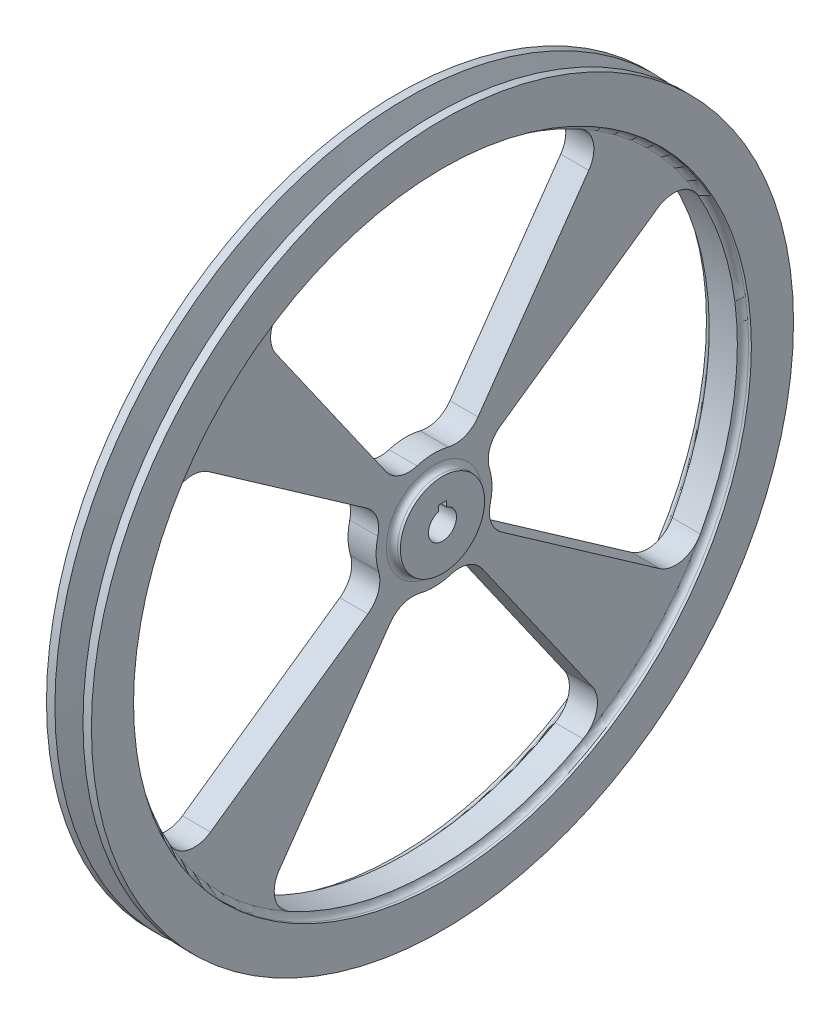
SolidWorks part; units mm, degrees
material "Alloy Steel (SS)"
ref_plane "Front Plane" through (0, 0, 0) normal (0, 0, 1) x (1, 0, 0)
ref_plane "Top Plane" through (0, 0, 0) normal (0, 1, 0) x (1, 0, 0)
ref_plane "Right Plane" through (0, 0, 0) normal (1, 0, 0) x (0, 0, -1)
sketch "Sketch1" plane through (0, 0, 0) normal (0, 1, 0) x (1, 0, 0)
  line L0 (-5, 15) -> (-5, 110)
  line L1 (-5, 110) -> (-8, 110)
  line L2 (-8, 110) -> (-8, 125)
  line L12 (8, 125) -> (8, 110)
  line L13 (8, 110) -> (5, 110)
  line L14 (5, 110) -> (5, 15)
  line L15 (5, 15) -> (8, 15)
  line L16 (8, 15) -> (8, 5)
  line L17 (8, 5) -> (-8, 5)
  line L18 (-8, 5) -> (-8, 15)
  line L19 (-8, 15) -> (-5, 15)
  line L20 (0, 0) -> (0, 100) construction
  line L21 (0, 0) -> (-66.9649, 0) construction
  line L22 (-5, 125) -> (-1.9427, 115)
  line L23 (-5, 125) -> (-8, 125)
  line L24 (5, 125) -> (8, 125)
  line L25 (-1.9427, 115) -> (1.9427, 115)
  line L26 (1.9427, 115) -> (5, 125)
  point P27 (0, 115)
  dimension "D2" = 16
  dimension "D3" = 10
  dimension "D7" = 3
  dimension "D8" = 10
  dimension "D11" = 5
  dimension "D12" = 16
  dimension "D14" = 100
  dimension "D16" = 15
  dimension "D17" = 34
  dimension "D18" = 10
revolve "Revolve1" add sketch "Sketch1" angle 360 about L21
fillet "Fillet1" radius 2 4 edges at (5, 0, -110) (-5, 0, -15) (-5, 0, -110) (5, 0, -15)
sketch "Sketch4" plane through (5, 0, 0) normal (1, 0, 0) x (0, 0, -1)
  line L0 (-17.1535, 23.5615) -> (-56.3877, 79.5938)
  line L1 (15.6635, 23.9764) -> (55.1055, 80.3054)
  line L2 (0, 0) -> (0, 64.8735) construction
  arc A7 (5.0332, 20.0141) -> (-6.0368, 19.7346) centre (0, 0) ccw
  arc A8 (51.7011, 94.8209) -> (-53.1142, 94.0366) centre (0, 0) ccw
  arc A9 (-6.0368, 19.7346) -> (-17.1535, 23.5615) centre (-8.962, 29.2972) cw
  arc A10 (5.0332, 20.0141) -> (15.6635, 23.9764) centre (7.472, 29.7122) ccw
  arc A11 (55.1055, 80.3054) -> (51.7011, 94.8209) centre (46.914, 86.0411) ccw
  arc A12 (-56.3877, 79.5938) -> (-53.1142, 94.0366) centre (-48.1962, 85.3295) cw
  circle A13 centre (0, 0) radius 108 construction
  point P16 (0, 0)
  dimension "D1" = 10
  dimension "D2" = 70
  dimension "D3" = 35
extrude "Cut-Extrude1" cut sketch "Sketch4" against normal blind 40
pattern_circular "CirPattern1" count 4 every 90 about axis through (0, 0, 0) along (1, 0, 0) of "Cut-Extrude1"
sketch "Sketch5" plane through (8, 0, 0) normal (1, 0, 0) x (0, 0, -1)
  line L6 (-1.5, 6.8) -> (1.5, 6.8)
  line L9 (-1.5, 6.8) -> (-1.5, 1.8)
  line L10 (-1.5, 1.8) -> (1.5, 1.8)
  line L11 (1.5, 6.8) -> (1.5, 1.8)
  point P4 (0, 0)
  point P5 (0, 1.8)
  dimension "D1" = 3
  dimension "D3" = 6.8
extrude "Cut-Extrude2" cut sketch "Sketch5" against normal through all
